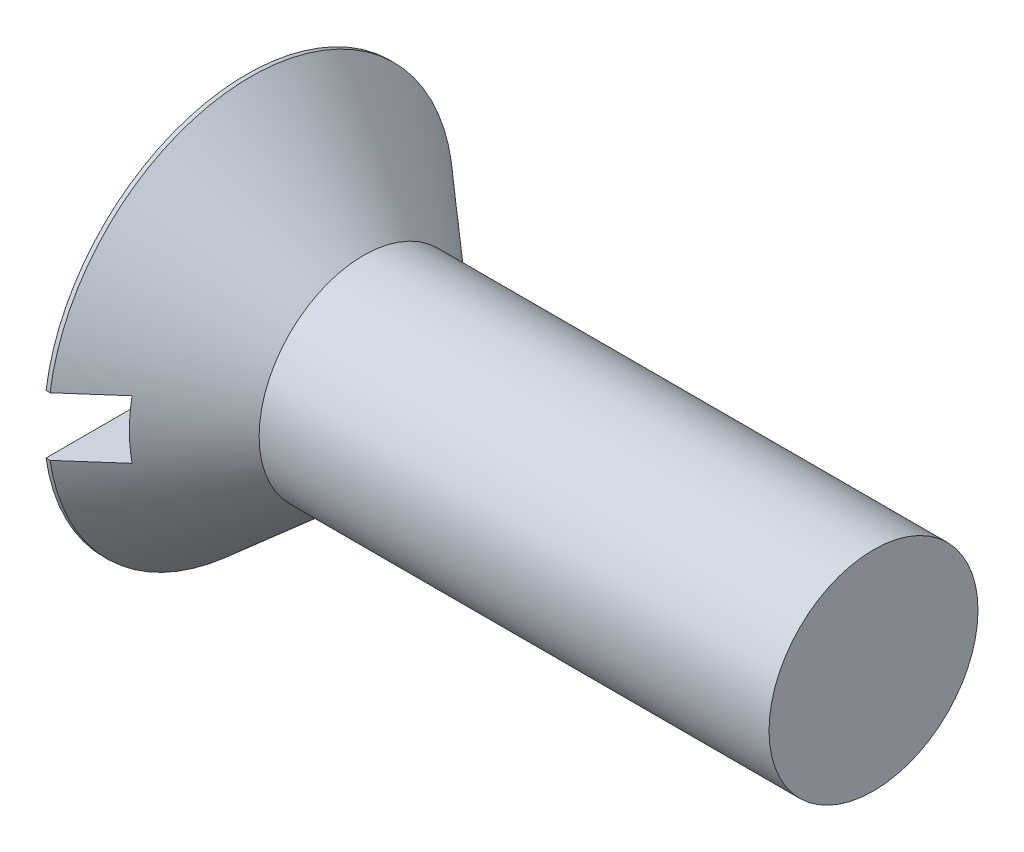
SolidWorks part; units mm, degrees
revolve "Base-Revolve" add sketch "BodySke" angle 360 about L5
sketch "BodySke" plane through (0, 0, 0) normal (0, 0, 1) x (1, 0, 0)
  line L0 (0, 0) -> (0, 6.1595)
  line L1 (0, 6.1595) -> (0.1227, 6.1595)
  line L2 (3.556, 3.175) -> (19.05, 3.175)
  line L3 (19.05, 3.175) -> (19.05, 0)
  line L4 (19.05, 0) -> (0, 0)
  line L5 (-6.35, 0) -> (82.55, 0) construction
  line L6 (3.556, -3.175) -> (19.05, -3.175) construction
  line L7 (0.1227, -6.1595) -> (3.556, -3.175) construction
  line L8 (0.1227, 6.1595) -> (3.556, 3.175)
  line L9 (0, -6.1595) -> (0.1227, -6.1595) construction
  line L10 (4.826, 4.7625) -> (4.826, -4.7625) construction
  line L11 (0, 6.35) -> (0, -3.175) construction
  dimension "Diameter" = 6.35
  dimension "Length" = 19.05
  dimension "Head_ht" = 3.556
  dimension "Head_dia" = 12.319
  dimension "Head_ang" = 82
  dimension "D6" = 0.1227
  dimension "Advance" = 1.27
  dimension "Thread_nom" = 19.05
cosmetic thread "ThreadCosmetic" [suppressed] parameters "Thread_length"=14.224, "Thread_minor"=4.8387
extrude "Slot" cut sketch "Sketch6" against normal blind 1.4478
sketch "Sketch6" plane through (0, 0, 0) normal (-1, 0, 0) x (0, 0, 1)
  line L0 (-6.1595, -0.889) -> (6.1595, -0.889)
  line L1 (-6.1595, -0.889) -> (-6.1595, 0.889)
  line L2 (6.1595, 0.889) -> (-6.1595, 0.889)
  line L3 (6.1595, 0.889) -> (6.1595, -0.889)
  dimension "Slot_width" = 1.778
  dimension "D1" = 0.889
  dimension "D2" = 12.319
  dimension "D3" = 6.1595
ref_plane "Plane1" through (0, 0, 0) normal (0, 0, 1) x (1, 0, 0)
ref_plane "Plane2" through (0, 0, 0) normal (0, 1, 0) x (1, 0, 0)
ref_plane "Plane3" through (0, 0, 0) normal (1, 0, 0) x (0, 0, -1)
sketch "ThdSchSke" plane through (0, 0, 0) normal (0, 0, 1) x (1, 0, 0)
  line L0 (4.826, -2.4194) -> (4.2969, -3.175)
  line L1 (4.826, -2.4194) -> (5.3551, -3.175)
  line L2 (5.3551, -3.175) -> (5.3551, -3.9688)
  line L3 (-3.175, 0) -> (5.1513, 0) construction
  line L5 (5.3551, -3.9688) -> (4.2969, -3.9688)
  line L6 (4.2969, -3.9688) -> (4.2969, -3.175)
  line L7 (0, 6.1595) -> (0, 0.889) construction
  dimension "Diameter" = 6.35
  dimension "Thread_minor" = 4.8387
  dimension "Start" = 4.826
revolve "ThreadSchematic" [suppressed] cut sketch "ThdSchSke" angle 360 about L3
pattern_linear "ThdSchPat" [suppressed]
equation "\"D1@Sketch6\" = \"Slot_width@Sketch6\" / 2"
equation "\"D2@Sketch6\" = \"Head_dia@BodySke\""
equation "\"D3@Sketch6\" = \"D2@Sketch6\" / 2"
equation "\"Thread_length@ThreadCosmetic\" = ((sgn( (\"Length@BodySke\" - \"Advance@BodySke\" - \"Head_ht@BodySke\" ) - \"Thread_nom@BodySke\" )-1)*( (\"Length@BodySke\" - \"Advance@BodySke\" - \"Head_ht@BodySke\" ) - \"Thread_nom@BodySke\" ))/-2+ \"Thread_nom@BodySke\""
equation "\"Thread_minor@ThdSchSke\" = \"Thread_minor@ThreadCosmetic\""
equation "\"Diameter@ThdSchSke\" = \"Diameter@BodySke\""
equation "\"Overcut@ThdSchSke\" = \"Diameter@BodySke\" * 1.25"
equation "\"Start@ThdSchSke\" = 0.000001 + \"Length@BodySke\" - \"Thread_length@ThreadCosmetic\"  '---Countersunk---"
equation "\"Num_threads@ThdSchPat\" = int( \"Thread_length@ThreadCosmetic\" / \"Advance@BodySke\" + 0.999 )  + 1"
equation "\"Advance@ThdSchPat\" = \"Thread_length@ThreadCosmetic\" /  (\"Num_threads@ThdSchPat\" - 1) 'relax it"
